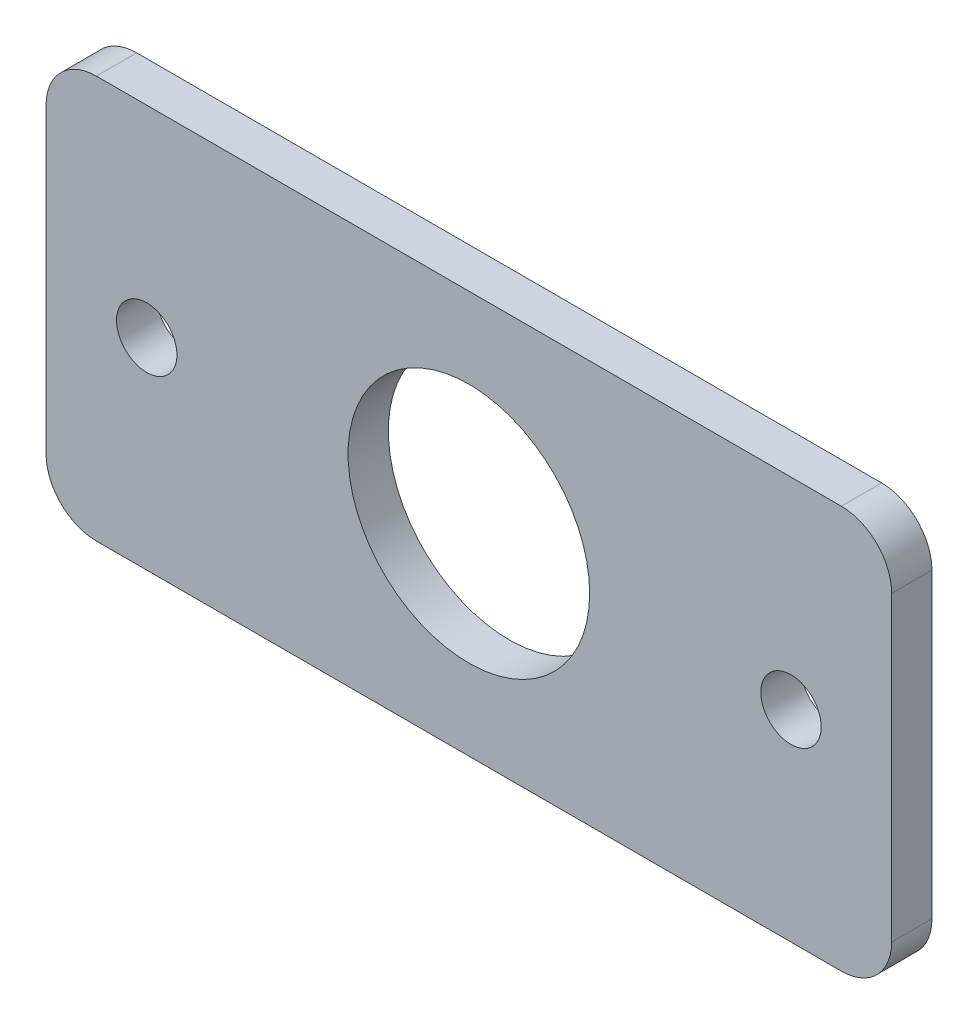
SolidWorks part; units mm, degrees
ref_plane "Front Plane" through (0, 0, 0) normal (0, 0, 1) x (1, 0, 0)
ref_plane "Top Plane" through (0, 0, 0) normal (0, 1, 0) x (1, 0, 0)
ref_plane "Right Plane" through (0, 0, 0) normal (1, 0, 0) x (0, 0, -1)
sketch "Model" plane through (0, 0, 0) normal (0, 0, 1) x (1, 0, 0)
  line L0 (0, 0) -> (0, 20) construction
  line L1 (-18.5, 20) -> (18.5, 20)
  line L2 (-21, 17.5) -> (-21, 2.5)
  line L3 (-18.5, 0) -> (18.5, 0)
  line L4 (21, 17.5) -> (21, 2.5)
  line L5 (-21, 10) -> (21, 10) construction
  arc A0 (-18.5, 20) -> (-21, 17.5) centre (-18.5, 17.5) ccw
  arc A1 (-21, 2.5) -> (-18.5, 0) centre (-18.5, 2.5) ccw
  arc A2 (18.5, 0) -> (21, 2.5) centre (18.5, 2.5) ccw
  arc A3 (21, 17.5) -> (18.5, 20) centre (18.5, 17.5) ccw
  circle A4 centre (16, 10) radius 1.5
  circle A5 centre (-16, 10) radius 1.5
  circle A6 centre (0, 10) radius 6
  dimension "D1" = 5
  dimension "D4" = 3
  dimension "D5" = 12
  dimension "D2" = 20
  dimension "D6" = 16
  dimension "D3" = 5
extrude "Boss-Extrude1" add sketch "Model" along normal blind 2
equation "\"acrylic-thickness\" = 2mm"
equation "\"linear-bar-bearingouter-dia\" = 15mm ' Diameter of the outer side of the bearing"
equation "\"spindle-thread-rbearing-diameter\" = 22mm ' Outer diameter of the rotational bearing"
equation "\"D1@Boss-Extrude1\" = \"acrylic-thickness\""
equation "\"D5@Model\"=\"linear-bar-bearingouter-dia\" - 3"
